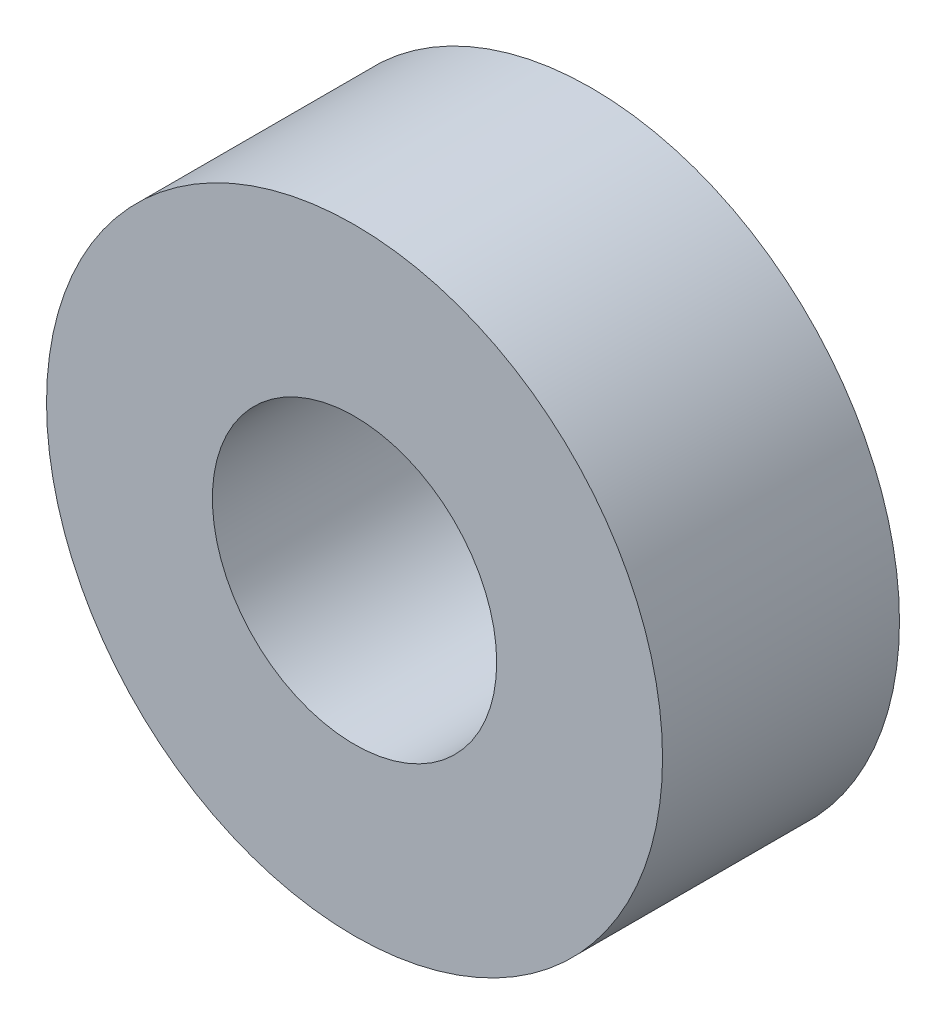
SolidWorks part; units mm, degrees
ref_plane "Front Plane" through (0, 0, 0) normal (0, 0, 1) x (1, 0, 0)
ref_plane "Top Plane" through (0, 0, 0) normal (0, 1, 0) x (1, 0, 0)
ref_plane "Right Plane" through (0, 0, 0) normal (1, 0, 0) x (0, 0, -1)
sketch "Sketch1" plane through (0, 0, 0) normal (0, 0, 1) x (1, 0, 0)
  circle A0 centre (0, 0) radius 6.5
  circle A1 centre (0, 0) radius 3
extrude "Ring_Envelope" add sketch "Sketch1" along normal blind 5
